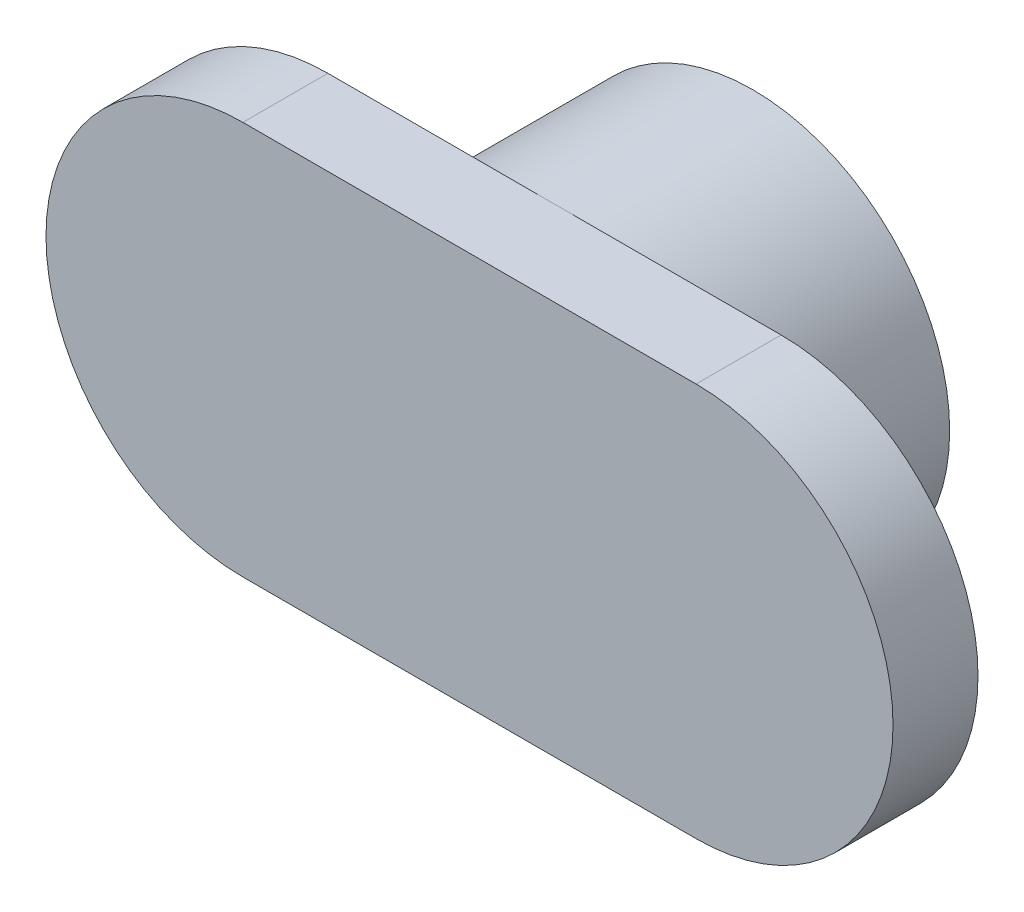
SolidWorks part; units mm, degrees
ref_plane "Ebene vorne" through (0, 0, 0) normal (0, 0, 1) x (1, 0, 0)
ref_plane "Ebene oben" through (0, 0, 0) normal (0, 1, 0) x (1, 0, 0)
ref_plane "Ebene rechts" through (0, 0, 0) normal (1, 0, 0) x (0, 0, -1)
sketch "Skizze1" plane through (0, 0, 0) normal (0, 0, 1) x (1, 0, 0)
  circle A0 centre (0, 0) radius 3.475
  dimension "D1" = 6.95
extrude "Aufsatz-Linear austragen1" add sketch "Skizze1" along normal blind 3.5
sketch "Skizze2" plane through (0, 0, 3.5) normal (0, 0, 1) x (1, 0, 0)
  line L0 (-4, 0) -> (4, 0) construction
  line L1 (-4, 3.475) -> (4, 3.475)
  line L2 (-4, -3.475) -> (4, -3.475)
  line L3 (0, 3.1373) -> (0, -3.5411) construction
  arc A1 (-4, 3.475) -> (-4, -3.475) centre (-4, 0) ccw
  arc A2 (4, -3.475) -> (4, 3.475) centre (4, 0) ccw
  point P3 (0, 0)
  point P9 (0, 0)
  dimension "D1" = 8
  dimension "D2" = 6.95
extrude "Aufsatz-Linear austragen2" add sketch "Skizze2" along normal blind 1.5
